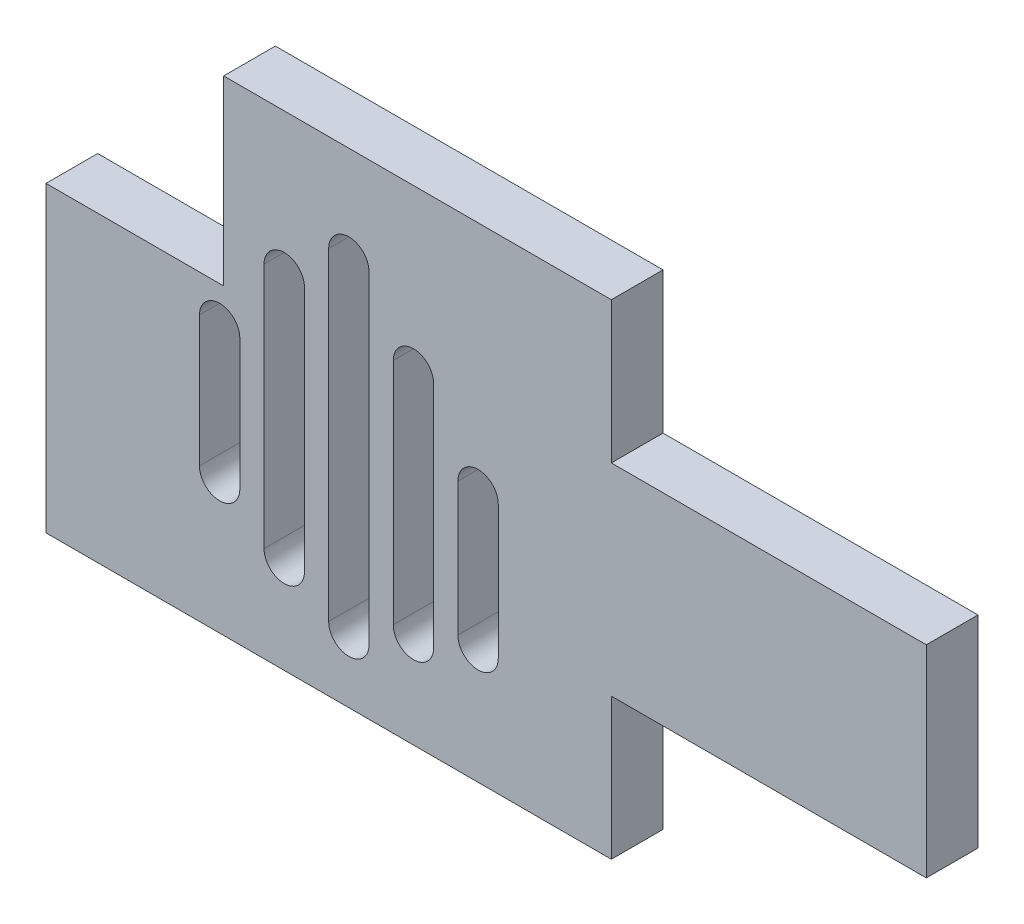
SolidWorks part; units mm, degrees
ref_plane "Front Plane" through (0, 0, 0) normal (0, 0, 1) x (1, 0, 0)
ref_plane "Top Plane" through (0, 0, 0) normal (0, 1, 0) x (1, 0, 0)
ref_plane "Right Plane" through (0, 0, 0) normal (1, 0, 0) x (0, 0, -1)
sketch "Sketch1" plane through (0, 0, 0) normal (0, 0, 1) x (1, 0, 0)
  line L0 (-4.1373, 38.9941) -> (-4.1373, -1.0059)
  line L6 (30.8627, 33.4941) -> (69.8627, 33.4941)
  line L9 (0.8627, 38.9941) -> (0.8627, -1.0059)
  line L12 (-12.1373, 33.3124) -> (-12.1373, 2.8098)
  line L15 (-7.1373, 33.3124) -> (-7.1373, 2.8098)
  line L18 (-15.1373, 23.8613) -> (-15.1373, 7.6834)
  line L21 (30.8627, 8.4941) -> (69.8627, 8.4941)
  line L62 (-17.1373, 50.9941) -> (-17.1373, 28.4723)
  line L63 (-17.1373, 28.4723) -> (-39.1373, 28.4723)
  line L65 (-39.1373, 28.4723) -> (-39.1373, -9.0059)
  line L66 (30.8627, 50.9941) -> (30.8627, 33.4941)
  line L68 (69.8627, 33.4941) -> (69.8627, 8.4941)
  line L70 (30.8627, 8.4941) -> (30.8627, -9.0059)
  line L71 (30.8627, 50.9941) -> (-17.1373, 50.9941)
  line L72 (30.8627, -9.0059) -> (-39.1373, -9.0059)
  line L75 (-20.1373, 23.8613) -> (-20.1373, 7.6834)
  line L77 (3.8627, 30.9941) -> (3.8627, 2.6474)
  line L79 (8.8627, 30.9941) -> (8.8627, 2.6474)
  line L80 (11.8627, 22.0483) -> (11.8627, 5.5385)
  line L81 (16.8627, 22.0483) -> (16.8627, 5.5385)
  circle A13 centre (-1.6373, 38.9941) radius 2.5 construction
  circle A14 centre (-1.6373, -1.0059) radius 2.5 construction
  arc A15 (-4.1373, 38.9941) -> (0.8627, 38.9941) centre (-1.6373, 38.9941) cw
  arc A16 (0.8627, -1.0059) -> (-4.1373, -1.0059) centre (-1.6373, -1.0059) cw
  circle A17 centre (6.3627, 30.9941) radius 2.5 construction
  circle A18 centre (6.3627, 2.6474) radius 2.5 construction
  circle A19 centre (-9.6373, 33.3124) radius 2.5 construction
  circle A20 centre (-9.6373, 2.8098) radius 2.5 construction
  circle A21 centre (-17.6373, 23.8613) radius 2.5 construction
  circle A22 centre (-17.6373, 7.6834) radius 2.5 construction
  circle A23 centre (14.3627, 22.0483) radius 2.5 construction
  circle A24 centre (14.3627, 5.5385) radius 2.5 construction
  arc A27 (-12.1373, 33.3124) -> (-7.1373, 33.3124) centre (-9.6373, 33.3124) cw
  arc A28 (-15.1373, 23.8613) -> (-20.1373, 23.8613) centre (-17.6373, 23.8613) ccw
  arc A29 (-20.1373, 7.6834) -> (-15.1373, 7.6834) centre (-17.6373, 7.6834) ccw
  arc A30 (-12.1373, 2.8098) -> (-7.1373, 2.8098) centre (-9.6373, 2.8098) ccw
  arc A31 (3.8627, 2.6474) -> (8.8627, 2.6474) centre (6.3627, 2.6474) ccw
  arc A32 (11.8627, 5.5385) -> (16.8627, 5.5385) centre (14.3627, 5.5385) ccw
  arc A33 (16.8627, 22.0483) -> (11.8627, 22.0483) centre (14.3627, 22.0483) ccw
  arc A34 (8.8627, 30.9941) -> (3.8627, 30.9941) centre (6.3627, 30.9941) ccw
  point P0 (0, 0)
  dimension "D3" = 5
  dimension "D4" = 3
  dimension "D5" = 3
  dimension "D6" = 3
  dimension "D7" = 3
  dimension "D9" = 12
  dimension "D8" = 25
  dimension "D10" = 13
  dimension "D11" = 60
  dimension "D12" = 8
  dimension "D14" = 22
  dimension "D15" = 39
  dimension "D16" = 48
  dimension "D23" = 40
extrude "Boss-Extrude1" add sketch "Sketch1" along normal blind 6.4
equation "\"m\"= 3mm"
